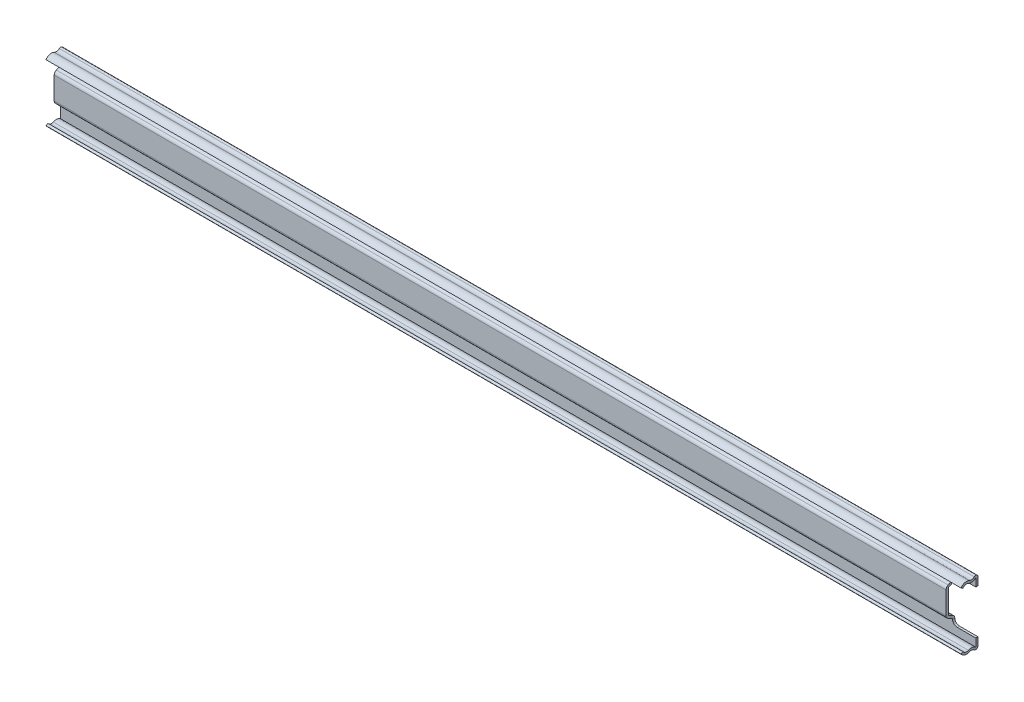
SolidWorks part; units mm, degrees
material "AISI 316 Annealed Stainless Steel Bar (SS)"
ref_plane "Front Plane" through (0, 0, 0) normal (0, 0, 1) x (1, 0, 0)
ref_plane "Top Plane" through (0, 0, 0) normal (0, 1, 0) x (1, 0, 0)
ref_plane "Right Plane" through (0, 0, 0) normal (1, 0, 0) x (0, 0, -1)
ref_plane "Plane1" through (-3.937, 0, 0) normal (1, 0, 0) x (0, 0, -1)
sketch "Sketch1" plane through (-3.937, 0, 0) normal (1, 0, 0) x (0, 0, -1)
  line L0 (2.3114, 16.3766) -> (2.3114, -16.3766)
  line L1 (-4.7105, -14.9753) -> (-5.7404, -15.6277)
  line L2 (3.5306, -16.3766) -> (3.5306, 16.3766)
  line L3 (-5.7404, 15.6277) -> (-4.7105, 14.9753)
  arc A0 (2.3114, -16.3766) -> (-1.7707, -15.816) centre (-0.1524, -19.1744) ccw
  arc A1 (-1.7707, -15.816) -> (-4.7105, -14.9753) centre (-2.7686, -13.7451) cw
  arc A2 (-5.7404, -15.6277) -> (-1.2415, -16.9143) centre (-2.7686, -13.7451) ccw
  arc A3 (-1.2415, -16.9143) -> (1.5056, -17.2916) centre (-0.1524, -19.1744) cw
  arc A4 (1.5056, -17.2916) -> (3.5306, -16.3766) centre (2.3114, -16.3766) ccw
  arc A5 (3.5306, 16.3766) -> (1.5056, 17.2916) centre (2.3114, 16.3766) ccw
  arc A6 (1.5056, 17.2916) -> (-1.2415, 16.9143) centre (-0.1524, 19.1744) cw
  arc A7 (-1.2415, 16.9143) -> (-5.7404, 15.6277) centre (-2.7686, 13.7451) ccw
  arc A8 (-4.7105, 14.9753) -> (-1.7707, 15.816) centre (-2.7686, 13.7451) cw
  arc A9 (-1.7707, 15.816) -> (2.3114, 16.3766) centre (-0.1524, 19.1744) ccw
  dimension "D1" = 3.728
  dimension "D2" = 2.2987
  dimension "D3" = 3.5179
  dimension "D4" = 1.2192
  dimension "D5" = 2.025
  dimension "D6" = 4.7721
  dimension "D7" = 8.2411
  dimension "D8" = 9.271
  dimension "D9" = 32.9195
  dimension "D10" = 34.1496
extrude "Boss-Extrude1" add sketch "Sketch1" against normal blind 500.126
sketch "Sketch2" plane through (0, 0, -3.5306) normal (0, 0, -1) x (-1, 0, 0)
  line L0 (3.937, 12.065) -> (3.937, -12.065)
  line L1 (3.937, -12.065) -> (16.637, -12.065)
  line L2 (16.637, -12.065) -> (16.637, 12.065)
  line L3 (16.637, 12.065) -> (3.937, 12.065)
  line L4 (3.937, -16.3766) -> (3.937, 16.3766) construction
  line L5 (504.063, -16.3766) -> (3.937, -16.3766) construction
  dimension "D1" = 12.7
  dimension "D2" = 4.3116
  dimension "D3" = 28.4416
extrude "Cut-Extrude1" cut sketch "Sketch2" against normal through all
sketch "Sketch3" plane through (0, 0, -2.3114) normal (0, 0, 1) x (1, 0, 0)
  line L0 (-504.063, -7.3781) -> (-504.063, 7.3781)
  line L1 (-504.063, 7.3781) -> (-16.637, 7.3781)
  line L2 (-16.637, 7.3781) -> (-16.637, -7.3781)
  line L3 (-16.637, -7.3781) -> (-504.063, -7.3781)
  line L4 (-504.063, 16.3766) -> (-504.063, -16.3766) construction
  line L5 (-504.063, 16.3766) -> (-3.937, 16.3766) construction
  dimension "D1" = 487.426
  dimension "D2" = 8.9985
  dimension "D3" = 23.7547
extrude "Boss-Extrude2" add sketch "Sketch3" along normal blind 3.556
sketch "Sketch4" plane through (-504.063, 0, 0) normal (-1, 0, 0) x (0, 0, 1)
  line L0 (-3.5306, 6.6014) -> (-3.5306, -6.6014)
  line L1 (-3.5306, -6.6014) -> (0.0254, -6.6014)
  line L2 (0.0254, -6.6014) -> (0.0254, 6.6014)
  line L3 (0.0254, 6.6014) -> (-3.5306, 6.6014)
  line L4 (-3.5306, -16.3766) -> (-3.5306, 16.3766) construction
  dimension "D1" = 3.556
  dimension "D2" = 10.6902
  dimension "D3" = 23.8929
extrude "Cut-Extrude2" cut sketch "Sketch4" against normal through all
draft "Draft1" type of draft neutral plane draft angle 25 faces to draft 2 face at (-260.35, 7.3781, -0.5334) face at (-260.35, -7.3781, -0.5334) neutral plane through (0, 0, 1.2446) neutral plane normal (0, 0, 1) parameters "D1"=25
draft "Draft2" type of draft neutral plane draft angle 25 faces to draft 2 face at (-260.35, 6.6014, -1.7526) face at (-260.35, -6.6014, -1.7526) neutral plane through (-3.937, -6.6014, 0.0254) neutral plane normal (0, 0, -1) parameters "D1"=25
fillet "Fillet1" radius 0.762 4 edges at (-260.35, 6.6014, 0.0254) (-260.35, -6.6014, 0.0254) (-260.35, 9.0363, -2.3114) (-260.35, -9.0363, -2.3114)
fillet "Fillet2" radius 1.9812 4 edges at (-260.35, 8.2596, -3.5306) (-260.35, 7.3781, 1.2446) (-260.35, -7.3781, 1.2446) (-260.35, -8.2596, -3.5306)
fillet "Fillet3" radius 2.54 2 edges at (-16.637, -12.065, -2.921) (-16.637, 12.065, -2.921)
